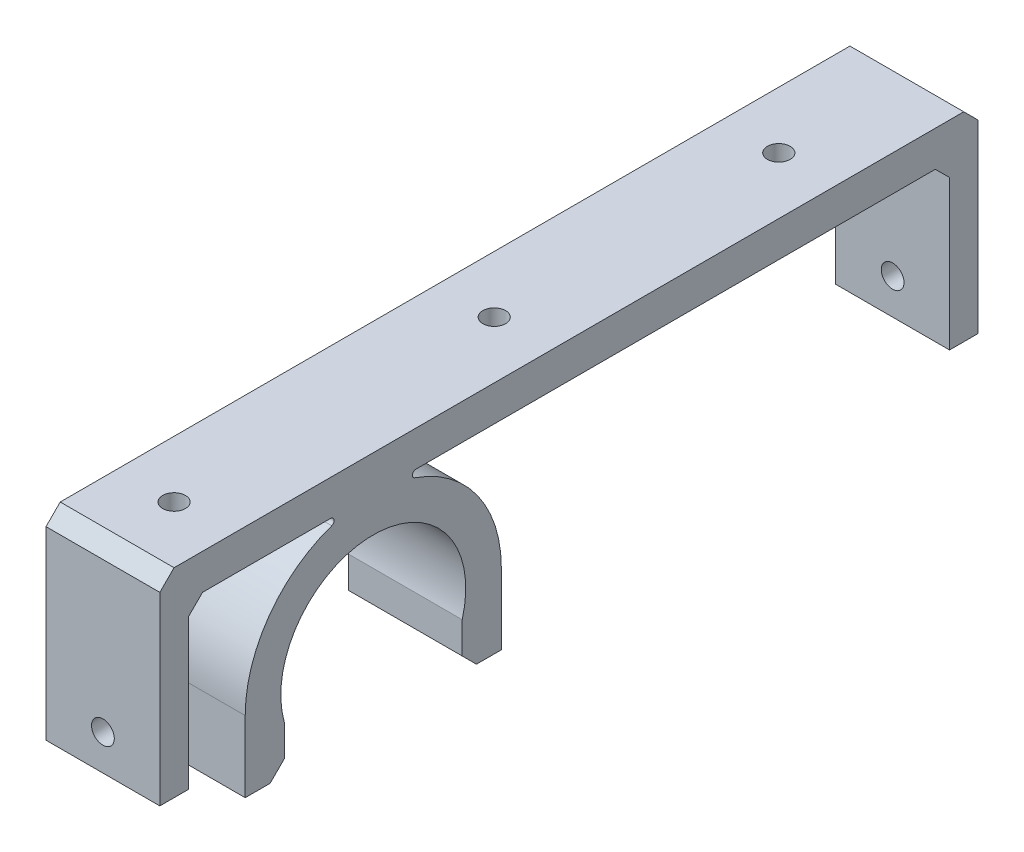
SolidWorks part; units mm, degrees
ref_plane "前视基准面" through (0, 0, 0) normal (0, 0, 1) x (1, 0, 0)
ref_plane "上视基准面" through (0, 0, 0) normal (0, 1, 0) x (1, 0, 0)
ref_plane "右视基准面" through (0, 0, 0) normal (1, 0, 0) x (0, 0, -1)
sketch "Sketch1" plane through (0, 0, 0) normal (1, 0, 0) x (0, 0, -1)
  line L0 (-12.5, -3.5707) -> (-12.5, -10)
  line L1 (-18, 0) -> (-18, -10)
  line L2 (-18, -10) -> (-12.5, -10)
  line L3 (12.5, -3.5707) -> (12.5, -10)
  line L4 (-6, 18) -> (-26, 18)
  line L5 (18, -10) -> (18, 0)
  line L6 (12.5, -10) -> (18, -10)
  line L7 (-30, 18) -> (-30, 23)
  line L8 (-30, 23) -> (85, 23)
  line L9 (85, 23) -> (85, 18)
  line L10 (81, 18) -> (6, 18)
  line L11 (0, 0) -> (0, 36.0866) construction
  line L12 (85, 18) -> (85, -5)
  line L13 (85, -5) -> (81, -5)
  line L14 (81, -5) -> (81, 18)
  line L15 (-30, 18) -> (-30, -5)
  line L16 (-30, -5) -> (-26, -5)
  line L17 (-26, -5) -> (-26, 18)
  arc A0 (12.5, -3.5707) -> (-12.5, -3.5707) centre (0, 0) ccw
  arc A1 (18, 0) -> (5.8378, 17.027) centre (0, 0) ccw
  arc A4 (-5.8378, 17.027) -> (-18, 0) centre (0, 0) ccw
  arc A5 (-5.8378, 17.027) -> (-6, 18) centre (-6, 17.5) ccw
  arc A7 (6, 18) -> (5.8378, 17.027) centre (6, 17.5) ccw
  point P4 (0, 0)
  dimension "D1" = 13
  dimension "D2" = 18
  dimension "D3" = 10
  dimension "D12" = 1
  dimension "D13" = 1
  dimension "D5" = 30
  dimension "D6" = 85
  dimension "D7" = 5
  dimension "D8" = 4
  dimension "D9" = 4
  dimension "D11" = 28
extrude "Boss-Extrude1" add sketch "Sketch1" along normal mid plane 16
chamfer "Chamfer1" distance 2 angle 45 2 edges at (0, 18, -81) (0, 18, 26)
chamfer "Chamfer2" distance 2 angle 45 4 edges at (0, -10, -12.5) (0, -10, 12.5) (0, 23, -85) (0, 23, 30)
sketch "Sketch2" plane through (0, 0, 30) normal (0, 0, 1) x (1, 0, 0)
  circle A0 centre (0, 0) radius 1.6
  dimension "D1" = 3.2
extrude "Cut-Extrude1" cut sketch "Sketch2" against normal up to next
sketch "Sketch3" plane through (0, 0, -85) normal (0, 0, -1) x (-1, 0, 0)
  circle A0 centre (0, 0) radius 1.6
  dimension "D1" = 3.2
extrude "Cut-Extrude2" cut sketch "Sketch3" against normal up to next
sketch "Sketch4" plane through (0, 23, 0) normal (0, 1, 0) x (1, 0, 0)
  circle A0 centre (0, 65) radius 1.6
  circle A1 centre (0, 25) radius 1.6
  circle A2 centre (0, -20) radius 1.6
  dimension "D3" = 3.2
  dimension "D1" = 40
  dimension "D2" = 85
  dimension "D4" = 20
extrude "Cut-Extrude3" cut sketch "Sketch4" against normal up to next
